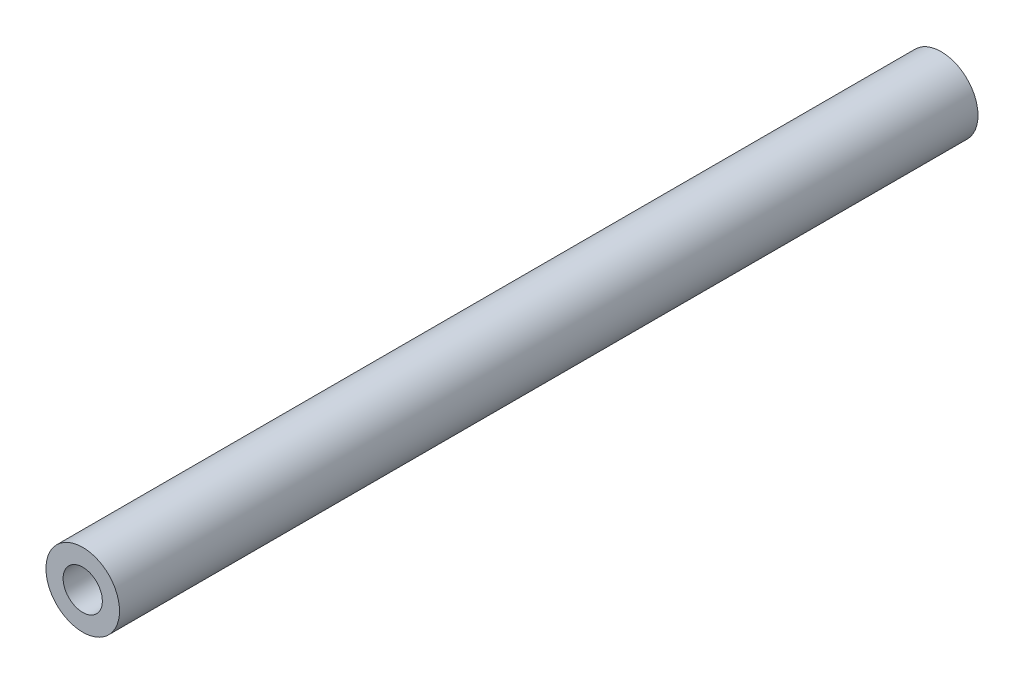
SolidWorks part; units mm, degrees
ref_plane "前视基准面" through (0, 0, 0) normal (0, 0, 1) x (1, 0, 0)
ref_plane "上视基准面" through (0, 0, 0) normal (0, 1, 0) x (1, 0, 0)
ref_plane "右视基准面" through (0, 0, 0) normal (1, 0, 0) x (0, 0, -1)
other "Configuration Table"
sketch "草图1" plane through (0, 0, 0) normal (0, 0, 1) x (1, 0, 0)
  circle A0 centre (0, 0) radius 3
  circle A1 centre (0, 0) radius 1.6
extrude "70mm铝柱" add sketch "草图1" along normal blind 70
